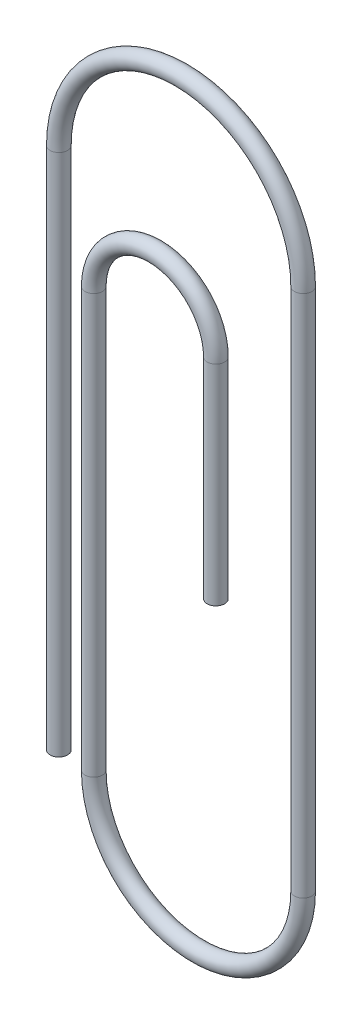
SolidWorks part; units mm, degrees
ref_plane "Front Plane" through (0, 0, 0) normal (0, 0, 1) x (1, 0, 0)
ref_plane "Top Plane" through (0, 0, 0) normal (0, 1, 0) x (1, 0, 0)
ref_plane "Right Plane" through (0, 0, 0) normal (1, 0, 0) x (0, 0, -1)
sketch "Sketch2" plane through (0, 0, 0) normal (0, 0, 1) x (1, 0, 0)
  line L2 (-83.6158, 41.8079) -> (-83.6158, -108.1921)
  line L4 (-13.6158, 41.8079) -> (-13.6158, -108.1921)
  line L6 (-13.6158, -108.1921) -> (-13.6158, 11.8079)
  line L8 (-73.6158, -108.1921) -> (-73.6158, 11.8079)
  line L10 (-73.6158, 11.8079) -> (-73.6158, -48.1921)
  line L12 (-38.6158, 11.8079) -> (-38.6158, -48.1921)
  arc A3 (-13.6158, 41.8079) -> (-83.6158, 41.8079) centre (-48.6158, 41.8079) ccw
  arc A4 (-13.6158, -108.1921) -> (-73.6158, -108.1921) centre (-43.6158, -108.1921) cw
  arc A5 (-73.6158, 11.8079) -> (-38.6158, 11.8079) centre (-56.1158, 11.8079) cw
  dimension "D1" = 150
  dimension "D2" = 70
  dimension "D4" = 60
  dimension "D5" = 120
  dimension "D7" = 60
  dimension "D8" = 35
sweep "Sweep2" add path "Sketch2" circular profile diameter 5 parameters "D3"=5
